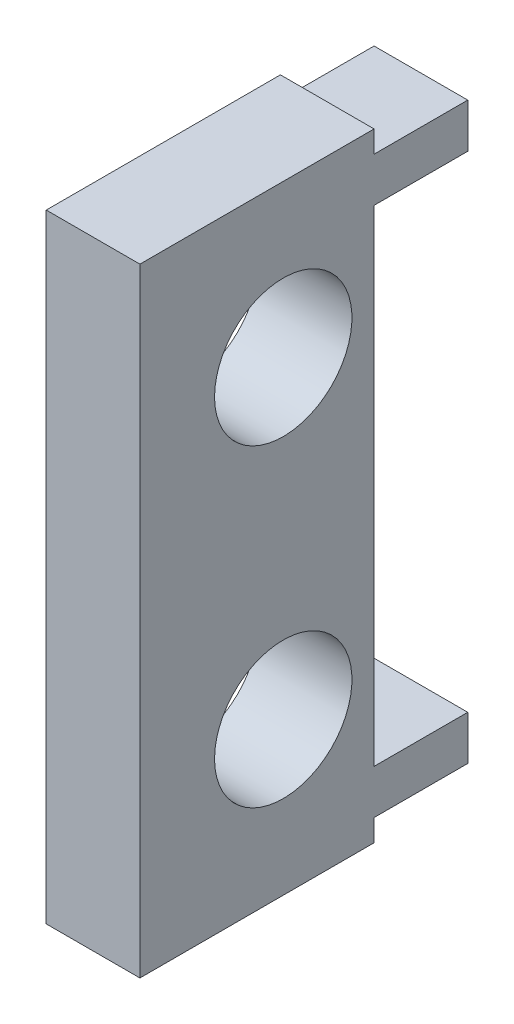
SolidWorks part; units mm, degrees
ref_plane "Alzado" through (0, 0, 0) normal (0, 0, 1) x (1, 0, 0)
ref_plane "Planta" through (0, 0, 0) normal (0, 1, 0) x (1, 0, 0)
ref_plane "Vista lateral" through (0, 0, 0) normal (1, 0, 0) x (0, 0, -1)
sketch "Croquis1" plane through (0, 0, 0) normal (0, 0, 1) x (1, 0, 0)
  line L1 (-1.5, -9.9) -> (1.5, -9.9)
  line L2 (-1.5, -9.9) -> (-1.5, 9.9)
  line L3 (-1.5, 9.9) -> (1.5, 9.9)
  line L4 (1.5, -9.9) -> (1.5, 9.9)
  line L5 (-1.5, -9.9) -> (1.5, 9.9) construction
  line L6 (-1.5, 9.9) -> (1.5, -9.9) construction
  point P0 (0, 0)
  dimension "D1" = 3
  dimension "D2" = 19.8
extrude "Saliente-Extruir1" add sketch "Croquis1" along normal blind 7.5
sketch "Croquis2" plane through (0, 0, 0) normal (0, 0, -1) x (-1, 0, 0)
  line L0 (0, -9.9) -> (0, 9.9) construction
  line L1 (1.5, -9.9) -> (-1.5, -9.9) construction
  line L2 (-1.5, 9.9) -> (1.5, 9.9) construction
  line L3 (1.5, 0) -> (-1.5, 0) construction
  line L4 (1.5, 9.9) -> (1.5, -9.9) construction
  line L5 (-1.5, -9.9) -> (-1.5, 9.9) construction
  line L6 (-1.5, 9.2) -> (-1.5, 7.78)
  line L7 (-1.5, -9.2) -> (1.5, -9.2)
  line L8 (-1.5, -9.2) -> (-1.5, -7.78)
  line L9 (-1.5, -7.78) -> (1.5, -7.78)
  line L10 (1.5, -9.2) -> (1.5, -7.78)
  line L11 (-1.5, -9.2) -> (1.5, -7.78) construction
  line L12 (-1.5, -7.78) -> (1.5, -9.2) construction
  line L13 (-1.5, 9.2) -> (1.5, 9.2)
  line L14 (1.5, 9.2) -> (1.5, 7.78)
  line L15 (-1.5, 7.78) -> (1.5, 7.78)
  point P12 (0, -8.49)
  dimension "D1" = 1.42
  dimension "D2" = 9.2
extrude "Saliente-Extruir2" add sketch "Croquis2" along normal blind 3
sketch "Croquis3" plane through (-1.5, 0, 0) normal (-1, 0, 0) x (0, 0, 1)
  line L0 (0, 0) -> (7.5, 0) construction
  line L1 (7.5, 9.9) -> (7.5, -9.9) construction
  line L2 (2.91, -9.9) -> (2.91, 9.9) construction
  line L3 (7.5, -9.9) -> (0, -9.9) construction
  line L4 (7.5, 9.9) -> (0, 9.9) construction
  circle A0 centre (2.91, -5.02) radius 2.2
  circle A1 centre (2.91, 5.02) radius 2.2
  dimension "D1" = 4.4
  dimension "D2" = 4.59
  dimension "D3" = 10.04
extrude "Cortar-Extruir1" cut sketch "Croquis3" against normal blind 3
